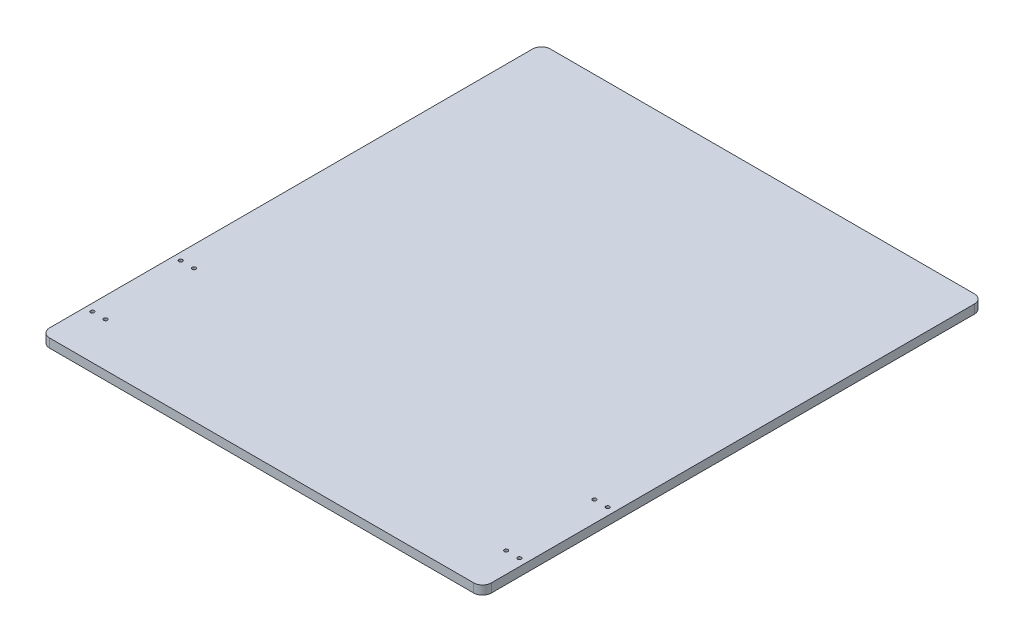
SolidWorks part; units mm, degrees
ref_plane "Front Plane" through (0, 0, 0) normal (0, 0, 1) x (1, 0, 0)
ref_plane "Top Plane" through (0, 0, 0) normal (0, 1, 0) x (1, 0, 0)
ref_plane "Right Plane" through (0, 0, 0) normal (1, 0, 0) x (0, 0, -1)
sketch "Sketch1" plane through (0, 0, 0) normal (0, 1, 0) x (1, 0, 0)
  line L1 (-150, 170) -> (150, 170)
  line L2 (-150, 170) -> (-150, -170)
  line L3 (-150, -170) -> (150, -170)
  line L4 (150, 170) -> (150, -170)
  line L5 (-150, 170) -> (150, -170) construction
  line L6 (-150, -170) -> (150, 170) construction
  point P0 (0, 0)
  dimension "D1" = 300
  dimension "D2" = 340
extrude "Boss-Extrude1" add sketch "Sketch1" along normal blind 6
fillet "Fillet1" radius 6 4 edges at (-150, 3, 170) (150, 3, 170) (-150, 3, -170) (150, 3, -170)
sketch "Sketch2" plane through (0, 6, 0) normal (0, 1, 0) x (1, 0, 0)
  line L0 (136, -80) -> (145, -80) construction
  line L1 (140.5, -140) -> (140.5, -170) construction
  line L2 (0, 170) -> (0, -170) construction
  line L3 (145, -80) -> (145, -140) construction
  line L4 (145, -140) -> (136, -140) construction
  line L5 (136, -140) -> (136, -80) construction
  line L6 (-144, -170) -> (144, -170) construction
  line L7 (145, -110) -> (150, -110) construction
  line L8 (150, -164) -> (150, 164) construction
  line L9 (144, 170) -> (-144, 170) construction
  line L10 (-145, -110) -> (-150, -110) construction
  line L11 (-136, -140) -> (-136, -80) construction
  line L12 (-145, -140) -> (-136, -140) construction
  line L13 (-145, -80) -> (-145, -140) construction
  line L14 (-140.5, -140) -> (-140.5, -170) construction
  line L15 (-136, -80) -> (-145, -80) construction
  circle A0 centre (136, -80) radius 1.25
  circle A1 centre (145, -80) radius 1.25
  circle A2 centre (145, -140) radius 1.25
  circle A3 centre (136, -140) radius 1.25
  circle A4 centre (-136, -140) radius 1.25
  circle A5 centre (-145, -140) radius 1.25
  circle A6 centre (-145, -80) radius 1.25
  circle A7 centre (-136, -80) radius 1.25
  dimension "D2" = 5
  dimension "D1" = 30
  dimension "D3" = 9
extrude "Cut-Extrude1" cut sketch "Sketch2" against normal through all
